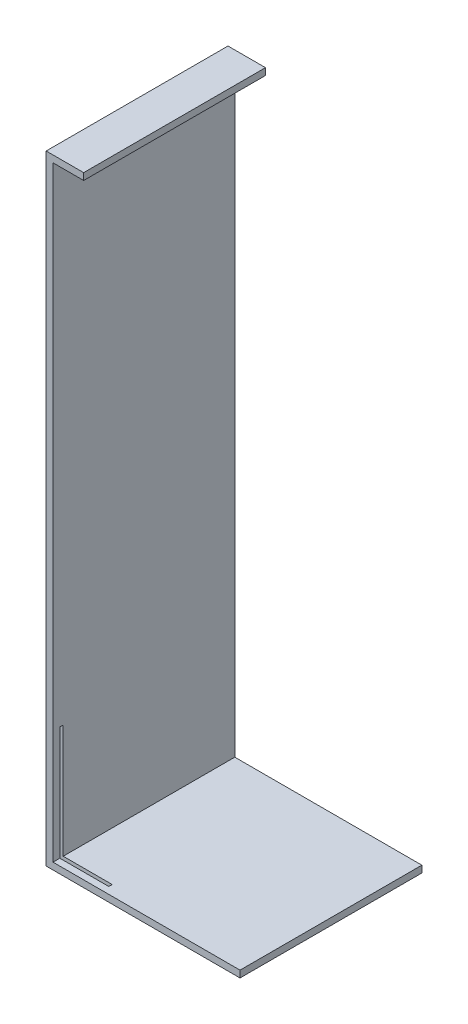
SolidWorks part; units mm, degrees
ref_plane "Front Plane" through (0, 0, 0) normal (0, 0, 1) x (1, 0, 0)
ref_plane "Top Plane" through (0, 0, 0) normal (0, 1, 0) x (1, 0, 0)
ref_plane "Right Plane" through (0, 0, 0) normal (1, 0, 0) x (0, 0, -1)
sketch "Sketch1" plane through (0, 0, 0) normal (0, 0, 1) x (1, 0, 0)
  line L0 (0, 220.665) -> (0, -51.835)
  line L1 (0, -51.835) -> (85.3, -51.835)
  line L2 (0, 220.665) -> (16.5, 220.665)
  line L3 (3, -48.835) -> (85.3, -48.835)
  line L4 (3, 217.665) -> (3, -48.835)
  line L5 (3, 217.665) -> (16.5, 217.665)
  line L6 (85.3, -48.835) -> (85.3, -51.835)
  line L7 (16.5, 220.665) -> (16.5, 217.665)
  dimension "D1" = 3
extrude "Boss-Extrude1" add sketch "Sketch1" against normal blind 80
sketch "Sketch2" plane through (3, 0, 0) normal (1, 0, 0) x (0, 0, -1)
  line L0 (80, -48.835) -> (0, -48.835) construction
  line L1 (3, -48.835) -> (4.5, -48.835)
  line L2 (3, -48.835) -> (3, 1.165)
  line L3 (3, 1.165) -> (4.5, 1.165)
  line L4 (4.5, -48.835) -> (4.5, 1.165)
  line L5 (0, -48.835) -> (0, 217.665) construction
  dimension "D1" = 50
  dimension "D2" = 1.5
  dimension "D3" = 3
extrude "Cut-Extrude1" cut sketch "Sketch2" against normal blind 1.5
sketch "Sketch3" plane through (0, -48.835, 0) normal (0, 1, 0) x (1, 0, 0)
  line L0 (2.8345, 3) -> (24.5634, 3)
  line L12 (1.5, 4.5) -> (24.5634, 4.5)
  line L13 (1.5, 4.5) -> (1.5, 3)
  line L14 (1.5, 3) -> (2.8345, 3)
  line L15 (24.5634, 4.5) -> (24.5634, 3)
  dimension "D1" = 1.5
extrude "Cut-Extrude3" cut sketch "Sketch3" against normal blind 1.5 contours L0 L15 L12 L13 L14
